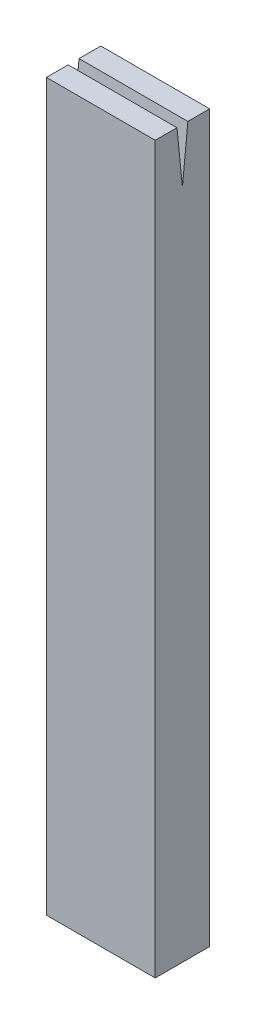
SolidWorks part; units mm, degrees
material "Pine"
ref_plane "Front Plane" through (0, 0, 0) normal (0, 0, 1) x (1, 0, 0)
ref_plane "Top Plane" through (0, 0, 0) normal (0, 1, 0) x (1, 0, 0)
ref_plane "Right Plane" through (0, 0, 0) normal (1, 0, 0) x (0, 0, -1)
sketch "Sketch1" plane through (0, 0, 0) normal (0, 1, 0) x (1, 0, 0)
  line L0 (-44.2539, 0) -> (44.2539, 0) construction
  line L1 (-30, 15) -> (30, 15)
  line L2 (-30, 15) -> (-30, -15)
  line L3 (-30, -15) -> (30, -15)
  line L4 (30, 15) -> (30, -15)
  line L5 (0, -44.7868) -> (0, 44.7868) construction
  point P4 (-30, 0)
  point P7 (0, -15)
  dimension "D1" = 30
  dimension "D2" = 60
extrude "Boss-Extrude1" add sketch "Sketch1" along normal blind 400
sketch "Sketch2" plane through (30, 0, 0) normal (1, 0, 0) x (0, 0, -1)
  line L0 (-3, 400) -> (0, 370)
  line L1 (-15, 400) -> (15, 400) construction
  line L2 (0, 370) -> (3, 400)
  line L3 (3, 400) -> (-3, 400)
  line L4 (-15, 400) -> (-15, 0) construction
  dimension "D1" = 30
  dimension "D2" = 15
  dimension "D3" = 3
  dimension "D4" = 6
extrude "Cut-Extrude1" cut sketch "Sketch2" against normal blind 60
